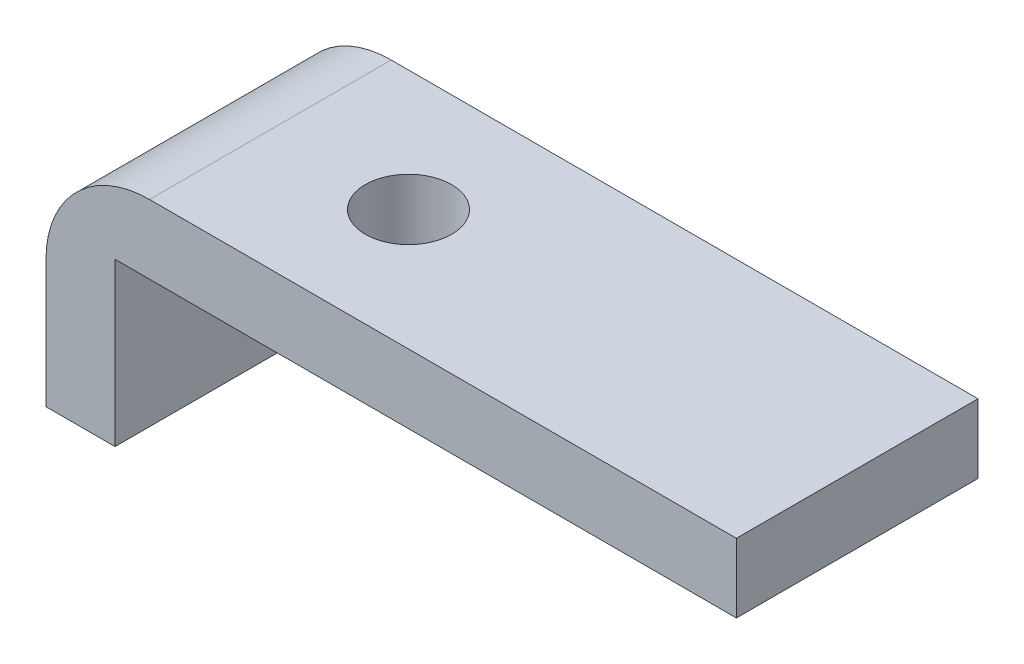
SolidWorks part; units mm, degrees
ref_plane "Спереди" through (0, 0, 0) normal (0, 0, 1) x (1, 0, 0)
ref_plane "Сверху" through (0, 0, 0) normal (0, 1, 0) x (1, 0, 0)
ref_plane "Справа" through (0, 0, 0) normal (1, 0, 0) x (0, 0, -1)
sketch "Эскиз1" plane through (0, 0, 0) normal (0, 0, 1) x (1, 0, 0)
  line L6 (8.5, 0) -> (-8.5, 0)
  line L11 (-11.5, -3) -> (-11.5, -6.7)
  line L12 (-11.5, -6.7) -> (-9.5, -6.7)
  line L13 (-9.5, -6.7) -> (-9.5, -2)
  line L14 (-9.5, -2) -> (8.5, -2)
  line L15 (8.5, -2) -> (8.5, 0)
  arc A0 (-8.5, 0) -> (-11.5, -3) centre (-8.5, -3) ccw
  point P9 (-11.5, 0)
  dimension "D4" = 3
  dimension "D1" = 20
  dimension "D2" = 2
  dimension "D3" = 6.7
extrude "Бобышка-Вытянуть1" add sketch "Эскиз1" along normal mid plane 7
hole_wizard "Отверстие обработанное метчиком M31" positions "Эскиз2" profile "Эскиз4" tap size "M3" standard "DIN" end condition through all
sketch "Эскиз2" plane through (0, -2, 0) normal (0, -1, 0) x (-1, 0, 0)
  line L0 (9.5, -3.5) -> (9.5, 3.5) construction
  point P0 (4.5, 0)
  dimension "D1" = 5
sketch "Эскиз4" plane through (-4.5, -2, 0) normal (1, 0, 0) x (0, 0, -1)
  line L0 (0, 0) -> (0, 2)
  line L1 (0, 2) -> (1.25, 2)
  line L2 (1.25, 2) -> (1.25, 0)
  line L5 (1.25, 0) -> (0, 0)
  line L11 (0, -6.35) -> (0, 107.95) construction
  dimension "Диаметр проходного сверла" = 2.5
  dimension "Глубина проходного сверла" = 2
cosmetic thread "Отверстие резьбы1"
